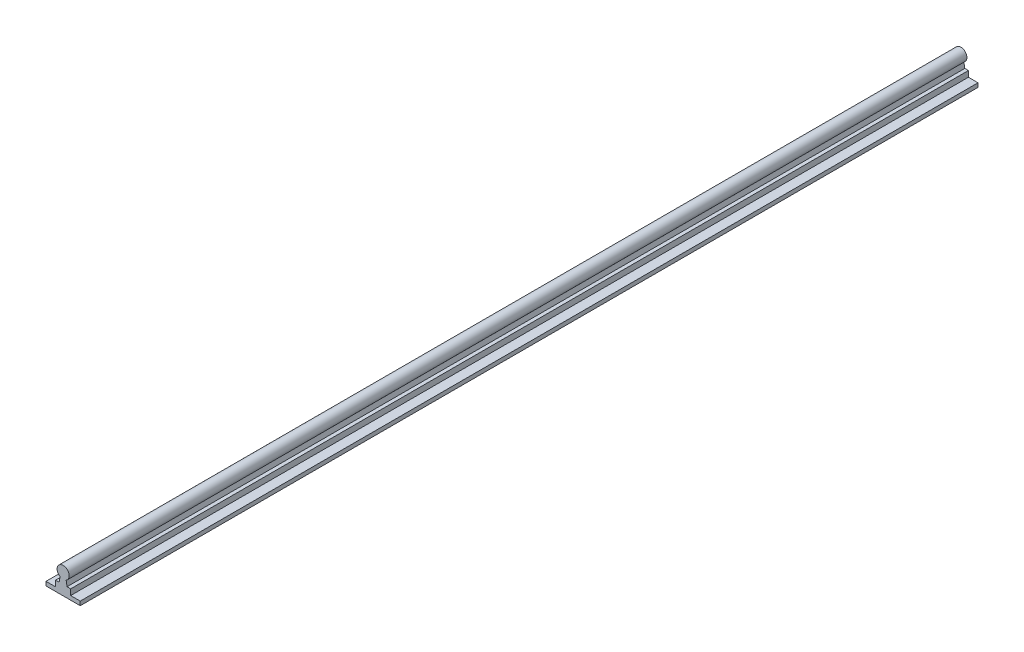
SolidWorks part; units mm, degrees
material "Chrome Stainless Steel"
ref_plane "Front Plane" through (0, 0, 0) normal (0, 0, 1) x (1, 0, 0)
ref_plane "Top Plane" through (0, 0, 0) normal (0, 1, 0) x (1, 0, 0)
ref_plane "Right Plane" through (0, 0, 0) normal (1, 0, 0) x (0, 0, -1)
sketch "Sketch1" plane through (0, 0, 0) normal (0, 0, 1) x (1, 0, 0)
  line L0 (21.3075, 0) -> (-12.6925, 0)
  line L1 (21.3075, 0) -> (21.3075, 4)
  line L2 (21.3075, 4) -> (11.8075, 4)
  line L3 (11.8075, 4) -> (11.8075, 9.8)
  line L4 (11.8075, 9.8) -> (8.2244, 9.8)
  line L5 (8.2244, 9.8) -> (7.3075, 15)
  line L6 (4.3075, 0) -> (4.3075, 36.0795) construction
  line L7 (0.3906, 9.8) -> (1.3075, 15)
  line L8 (-3.1925, 9.8) -> (0.3906, 9.8)
  line L9 (-3.1925, 4) -> (-3.1925, 9.8)
  line L10 (-12.6925, 0) -> (-12.6925, 4)
  line L11 (-12.6925, 4) -> (-3.1925, 4)
  arc A0 (7.3075, 15) -> (1.3075, 15) centre (4.3075, 20.1962) ccw
  point P17 (4.3075, 0)
  dimension "D5" = 6
  dimension "D1" = 17
  dimension "D2" = 4
  dimension "D3" = 9.8
  dimension "D4" = 15
  dimension "D6" = 3
  dimension "D8" = 20.1962
  dimension "D9" = 7.5
extrude "Boss-Extrude1" add sketch "Sketch1" along normal blind 891.7
